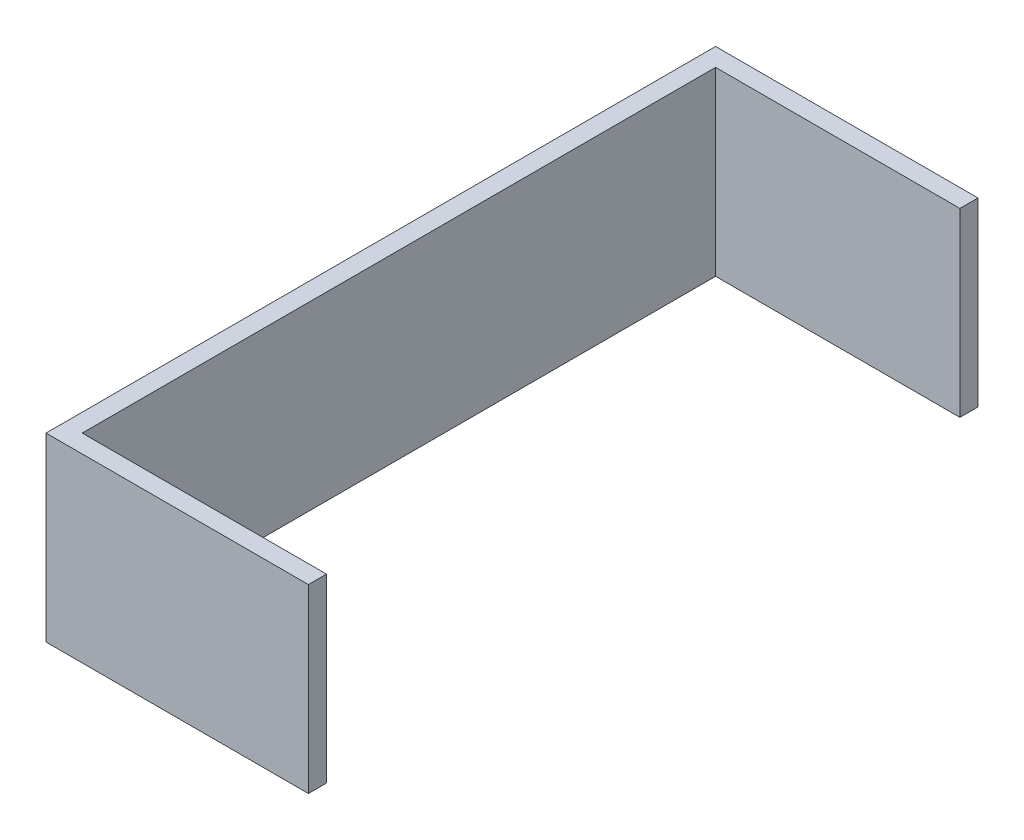
SolidWorks part; units mm, degrees
ref_plane "Front Plane" through (0, 0, 0) normal (0, 0, 1) x (1, 0, 0)
ref_plane "Top Plane" through (0, 0, 0) normal (0, 1, 0) x (1, 0, 0)
ref_plane "Right Plane" through (0, 0, 0) normal (1, 0, 0) x (0, 0, -1)
sketch "Sketch3" plane through (0, 0, 0) normal (0, 1, 0) x (1, 0, 0)
  line L0 (-145, 370) -> (145, 370)
  line L1 (-125, 350) -> (125, 350)
  line L2 (-125, 350) -> (-125, -350)
  line L3 (-125, -350) -> (125, -350)
  line L5 (-125, 350) -> (125, -350) construction
  line L6 (-125, -350) -> (125, 350) construction
  line L7 (145, 370) -> (145, 350)
  line L8 (-145, -370) -> (145, -370)
  line L9 (-145, 370) -> (-145, -370)
  line L10 (125, 350) -> (145, 350)
  line L11 (125, -350) -> (145, -350)
  line L12 (145, -350) -> (145, -370)
  line L13 (125, 350) -> (125, -350) construction
  line L14 (145, 370) -> (145, -370) construction
  point P0 (0, 0)
  dimension "D1" = 700
  dimension "D2" = 250
  dimension "D3" = 20
extrude "Boss-Extrude1" add sketch "Sketch3" along normal blind 200
